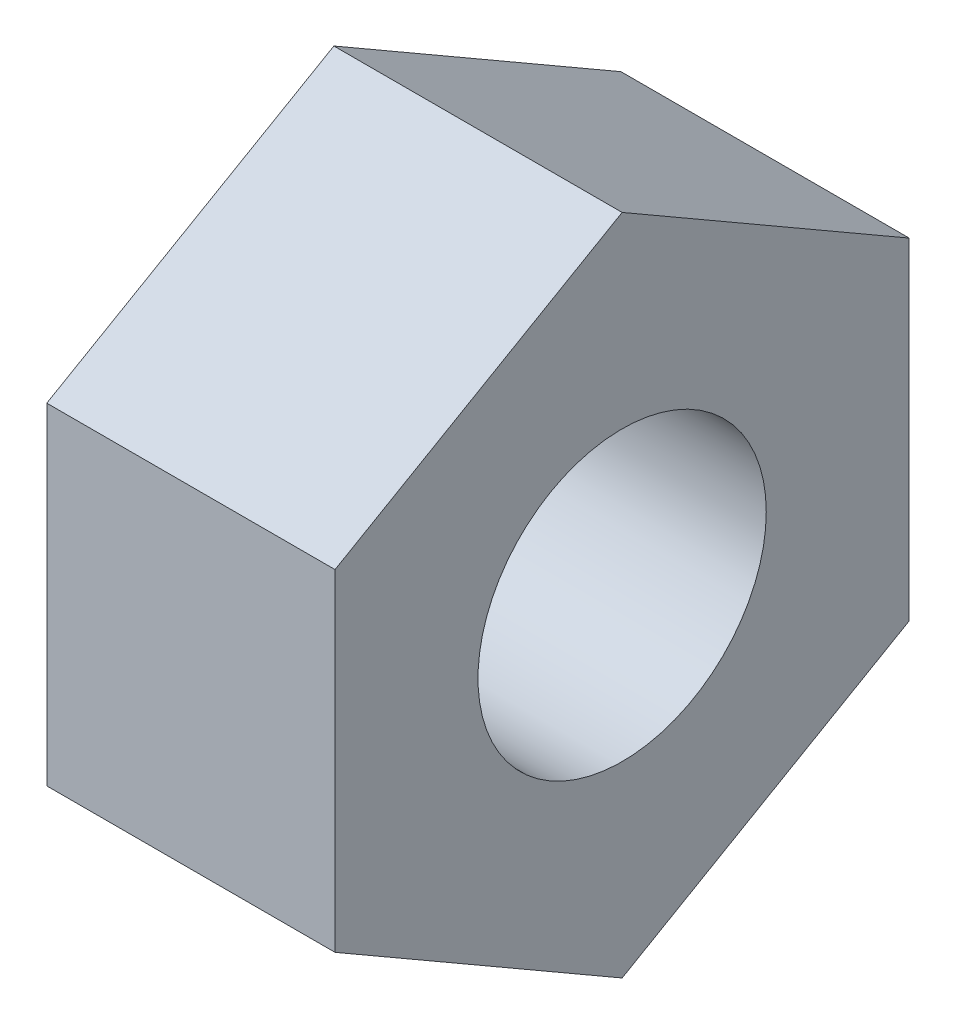
SolidWorks part; units mm, degrees
ref_plane "Front Plane" through (0, 0, 0) normal (1, 0, 0) x (0, 1, 0)
ref_plane "Top Plane" through (0, 0, 0) normal (0, 0, 1) x (0, 1, 0)
ref_plane "Right Plane" through (0, 0, 0) normal (0, 1, 0) x (-1, 0, 0)
sketch "Sketch1" plane through (0, 0, 0) normal (1, 0, 0) x (0, 1, 0)
  line L1 (11.5, 0) -> (5.75, 9.9593)
  line L2 (5.75, 9.9593) -> (-5.75, 9.9593)
  line L3 (-5.75, 9.9593) -> (-11.5, 0)
  line L4 (-11.5, 0) -> (-5.75, -9.9593)
  line L5 (-5.75, -9.9593) -> (5.75, -9.9593)
  line L6 (5.75, -9.9593) -> (11.5, 0)
  circle A0 centre (0, 0) radius 9.9593 construction
  circle A1 centre (0, 0) radius 5
  dimension "D2" = 10
  dimension "D1" = 11.5
extrude "Boss-Extrude1" add sketch "Sketch1" along normal blind 10
